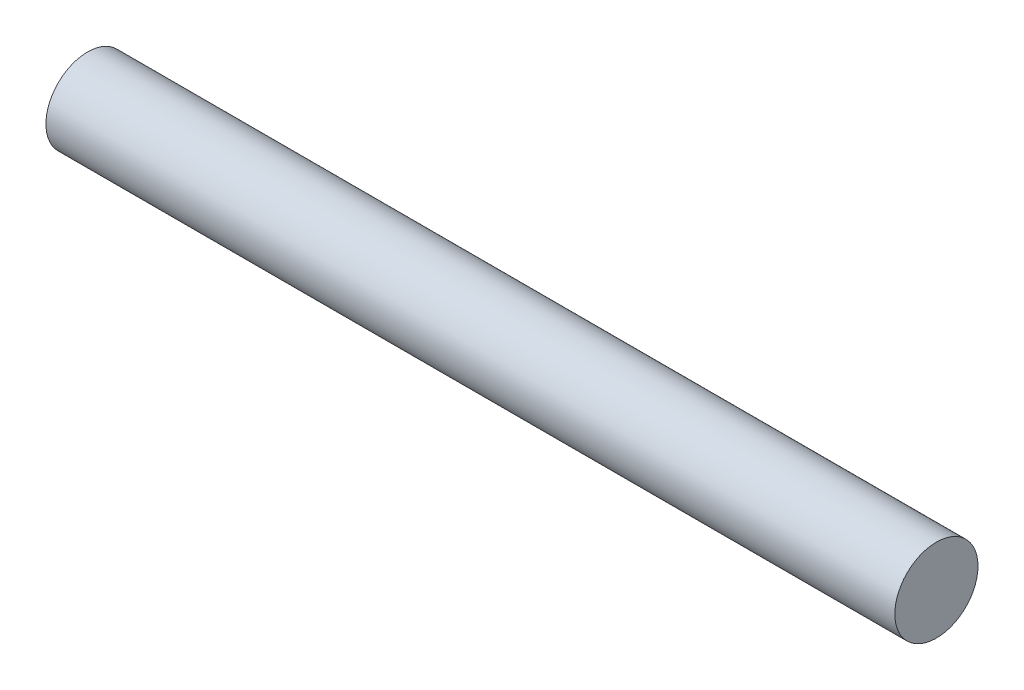
SolidWorks part; units mm, degrees
ref_plane "Front Plane" through (0, 0, 0) normal (1, 0, 0) x (0, 1, 0)
ref_plane "Top Plane" through (0, 0, 0) normal (0, 0, 1) x (0, 1, 0)
ref_plane "Right Plane" through (0, 0, 0) normal (0, 1, 0) x (-1, 0, 0)
sketch "Sketch1" plane through (0, 0, 0) normal (1, 0, 0) x (0, 1, 0)
  circle A0 centre (0, 0) radius 4.9
extrude "Boss-Extrude1" add sketch "Sketch1" along normal blind 100
sketch "Sketch2" plane through (0, 0, 0) normal (-1, 0, 0) x (0, -1, 0)
  line L0 (-1.85, -1.2806) -> (-1.85, 1.2806)
  line L1 (-1.85, 0) -> (1.85, 0) construction
  line L2 (1.85, -1.2806) -> (1.85, 1.2806)
  arc A1 (-1.85, 1.2806) -> (1.85, 1.2806) centre (0, 0) cw
  arc A2 (-1.85, -1.2806) -> (1.85, -1.2806) centre (0, 0) ccw
  point P8 (0, 0)
  dimension "D1" = 0
  dimension "D2" = 3.7
extrude "Cut-Extrude1" cut sketch "Sketch2" against normal blind 10
